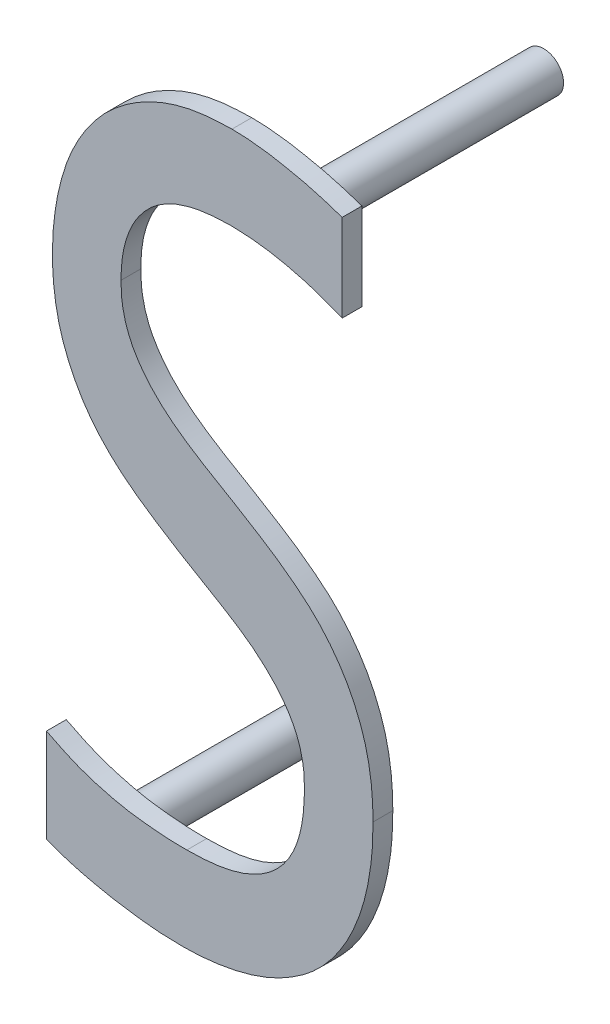
SolidWorks part; units mm, degrees
ref_plane "Front Plane" through (0, 0, 0) normal (0, 0, 1) x (1, 0, 0)
ref_plane "Top Plane" through (0, 0, 0) normal (0, 1, 0) x (1, 0, 0)
ref_plane "Right Plane" through (0, 0, 0) normal (1, 0, 0) x (0, 0, -1)
sketch "Sketch1" plane through (0, 0, 0) normal (0, 0, 1) x (1, 0, 0)
  text T0 "S" font "Consolas" height 914.4
extrude "Boss-Extrude1" add sketch "Sketch1" along normal blind 25.4
sketch "Sketch2" plane through (0, 0, 0) normal (0, 0, -1) x (-1, 0, 0)
  circle A0 centre (-360.2209, 860.8449) radius 25.4
  circle A1 centre (-120.3899, 47.6248) radius 25.4
  dimension "D1" = 50.8
  dimension "D2" = 50.8
extrude "Boss-Extrude2" add sketch "Sketch2" along normal blind 304.8
